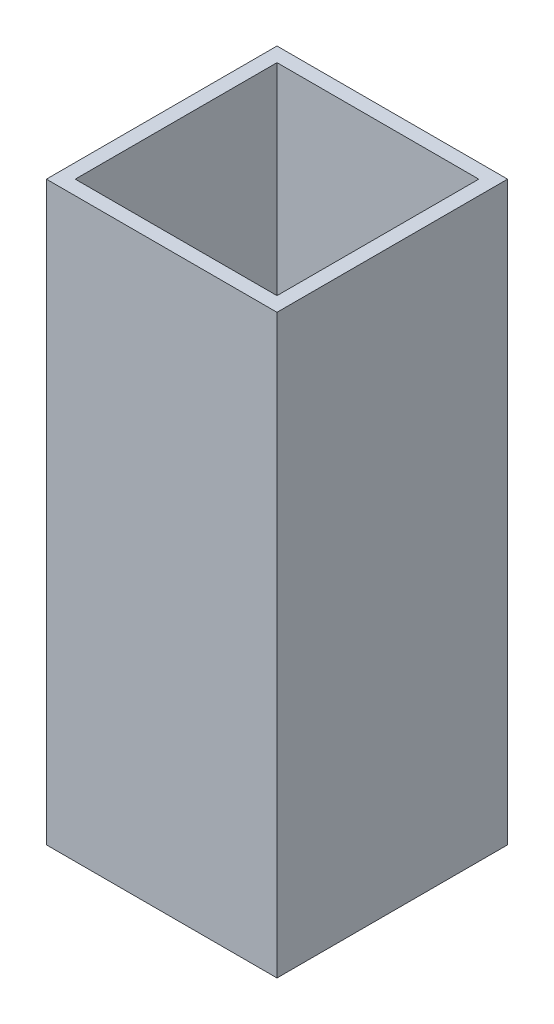
SolidWorks part; units mm, degrees
material "6061 Alloy"
ref_plane "Front Plane" through (0, 0, 0) normal (0, 0, 1) x (1, 0, 0)
ref_plane "Top Plane" through (0, 0, 0) normal (0, 1, 0) x (1, 0, 0)
ref_plane "Right Plane" through (0, 0, 0) normal (1, 0, 0) x (0, 0, -1)
sketch "Sketch1" plane through (0, 0, 0) normal (0, 1, 0) x (1, 0, 0)
  line L1 (12.7, 12.7) -> (-12.7, 12.7)
  line L2 (12.7, 12.7) -> (12.7, -12.7)
  line L3 (12.7, -12.7) -> (-12.7, -12.7)
  line L4 (-12.7, 12.7) -> (-12.7, -12.7)
  line L5 (12.7, 12.7) -> (-12.7, -12.7) construction
  line L6 (12.7, -12.7) -> (-12.7, 12.7) construction
  line L7 (11.1125, 11.1125) -> (-11.1125, 11.1125)
  line L8 (11.1125, 11.1125) -> (11.1125, -11.1125)
  line L9 (11.1125, -11.1125) -> (-11.1125, -11.1125)
  line L10 (-11.1125, 11.1125) -> (-11.1125, -11.1125)
  line L11 (11.1125, 11.1125) -> (-11.1125, -11.1125) construction
  line L12 (11.1125, -11.1125) -> (-11.1125, 11.1125) construction
  point P0 (0, 0)
  point P6 (0, 0)
  dimension "D1" = 25.4
  dimension "D2" = 25.4
  dimension "D3" = 1.5875
  dimension "D4" = 1.5875
extrude "Boss-Extrude1" add sketch "Sketch1" along normal blind 63.5
